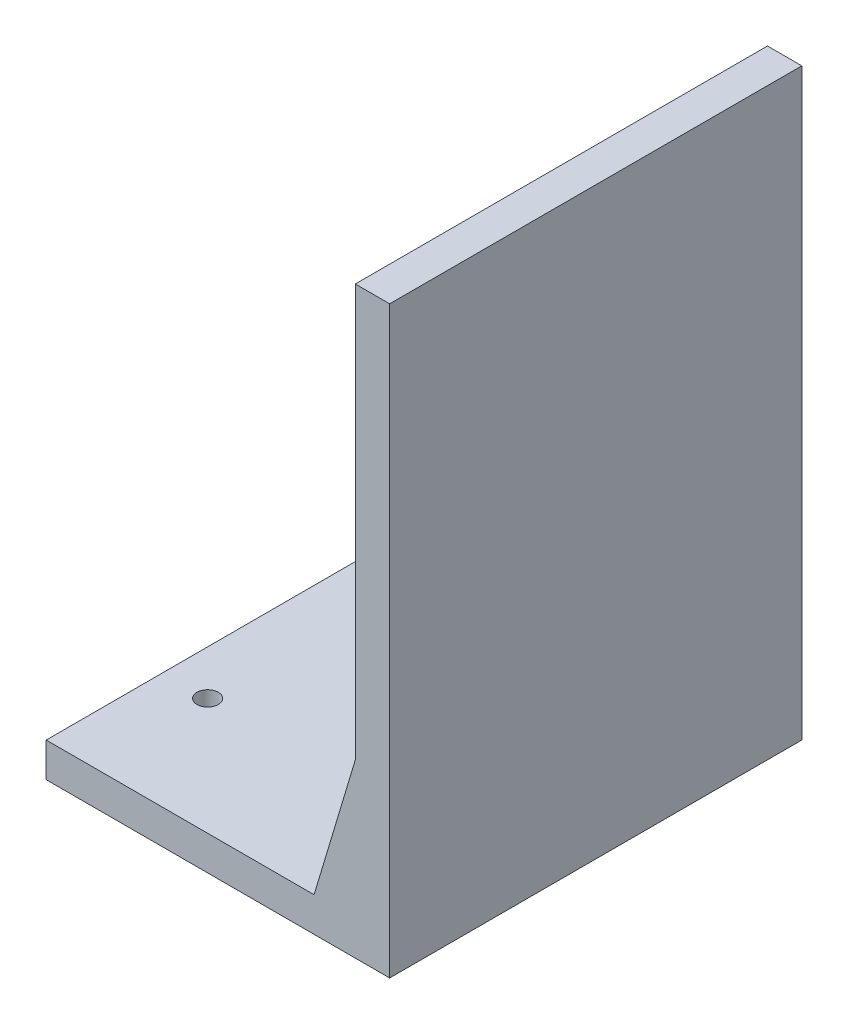
SolidWorks part; units mm, degrees
ref_plane "前视基准面" through (0, 0, 0) normal (0, 0, 1) x (1, 0, 0)
ref_plane "上视基准面" through (0, 0, 0) normal (0, 1, 0) x (1, 0, 0)
ref_plane "右视基准面" through (0, 0, 0) normal (1, 0, 0) x (0, 0, -1)
sketch "草图2" plane through (0, 0, 0) normal (0, 1, 0) x (1, 0, 0)
  line L1 (0, 0) -> (50, 0)
  line L2 (0, 0) -> (0, 60)
  line L3 (0, 60) -> (50, 60)
  line L4 (50, 0) -> (50, 60)
  dimension "D1" = 60
  dimension "D2" = 50
extrude "凸台-拉伸1" add sketch "草图2" along normal blind 5
sketch "草图3" plane through (0, 5, 0) normal (0, 1, 0) x (1, 0, 0)
  line L0 (50, 60) -> (0, 60) construction
  line L1 (50, 0) -> (45, 0)
  line L2 (50, 0) -> (50, 60)
  line L3 (50, 60) -> (45, 60)
  line L4 (45, 0) -> (45, 60)
  dimension "D1" = 5
extrude "凸台-拉伸2" add sketch "草图3" along normal blind 80
sketch "草图4" plane through (0, 0, 0) normal (0, 0, 1) x (1, 0, 0)
  line L0 (39, 5) -> (45, 25)
  line L1 (0, 5) -> (45, 5) construction
  line L2 (45, 85) -> (45, 5) construction
  line L3 (45, 25) -> (45, 5)
  line L4 (45, 5) -> (39, 5)
  dimension "D1" = 6
  dimension "D2" = 20
extrude "凸台-拉伸3" add sketch "草图4" against normal blind 10
sketch "草图5" plane through (0, 0, -60) normal (0, 0, -1) x (-1, 0, 0)
  line L0 (-39, 5) -> (-45, 25)
  line L1 (-45, 25) -> (-45, 5)
  line L2 (-45, 5) -> (-39, 5)
extrude "凸台-拉伸4" add sketch "草图5" against normal blind 10
ref_plane "基准面1" through (0, 0, -30) normal (0, 0, -1) x (-1, 0, 0)
sketch "草图6" plane through (0, 0, -30) normal (0, 0, -1) x (-1, 0, 0)
  line L0 (-39, 5) -> (-45, 25)
  line L1 (-45, 25) -> (-45, 5)
  line L2 (-45, 5) -> (-39, 5)
extrude "凸台-拉伸5" add sketch "草图6" along normal mid plane 10
sketch "草图7" plane through (0, 5, 0) normal (0, 1, 0) x (1, 0, 0)
  line L0 (19.5, 60) -> (19.5, 0) construction
  line L1 (39, 60) -> (0, 60) construction
  line L2 (0, 0) -> (39, 0) construction
  line L3 (0, 30) -> (45.2981, 30) construction
  line L4 (0, 60) -> (0, 0) construction
  line L5 (27.5, 30) -> (-27.5, 30) construction
  circle A0 centre (6.5, 43) radius 1.55
  circle A1 centre (32.5, 43) radius 1.55
  circle A2 centre (6.5, 17) radius 1.55
  circle A3 centre (32.5, 17) radius 1.55
  dimension "D1" = 3.1
  dimension "D2" = 26
  dimension "D3" = 26
extrude "切除-拉伸1" cut sketch "草图7" against normal through all
